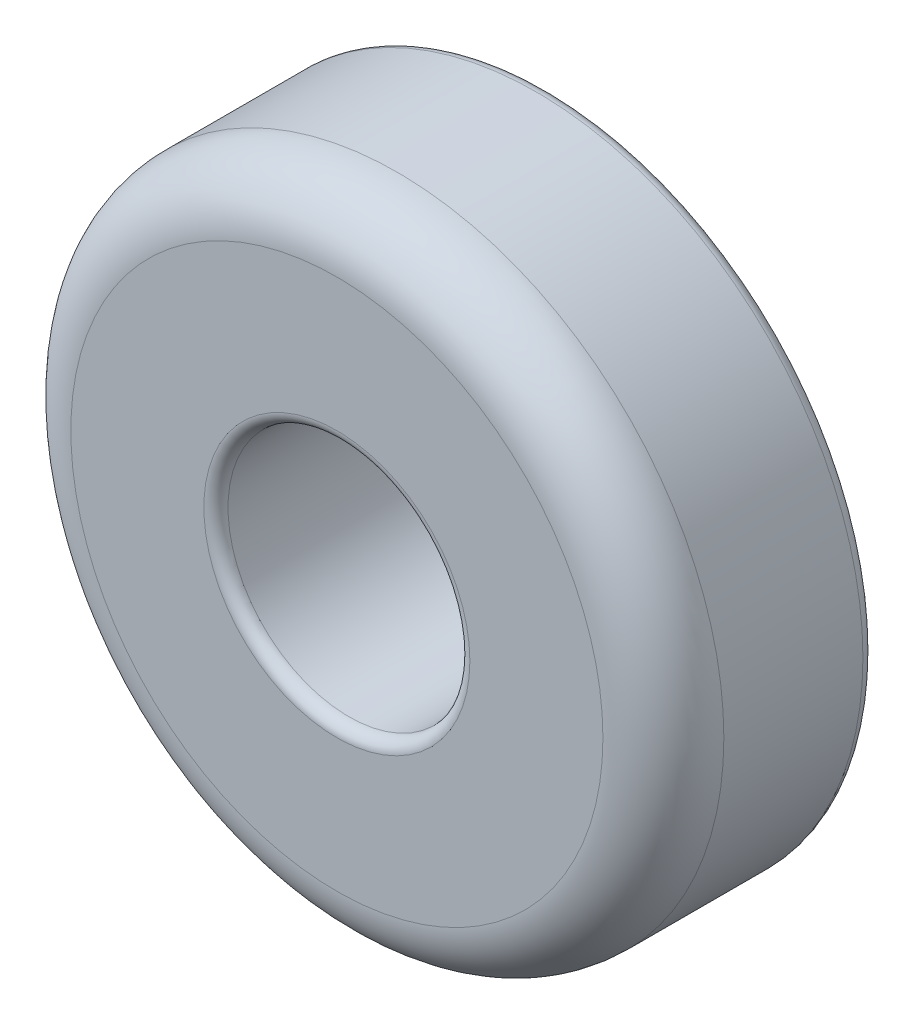
SolidWorks part; units mm, degrees
ref_plane "Front Plane" through (0, 0, 0) normal (0, 0, 1) x (1, 0, 0)
ref_plane "Top Plane" through (0, 0, 0) normal (0, 1, 0) x (1, 0, 0)
ref_plane "Right Plane" through (0, 0, 0) normal (1, 0, 0) x (0, 0, -1)
sketch "Sketch1" plane through (0, 0, 0) normal (0, 0, 1) x (1, 0, 0)
  circle A0 centre (0, 0) radius 1
  dimension "D1" = 2
extrude "Extrude-Thin1" add sketch "Sketch1" along normal blind 1.75 thin
fillet "Fillet1" radius 0.5 1 edges at (2.7, 0, 1.75)
fillet "Fillet2" radius 0.1 2 edges at (1, 0, 1.75) (2.7, 0, 0)
